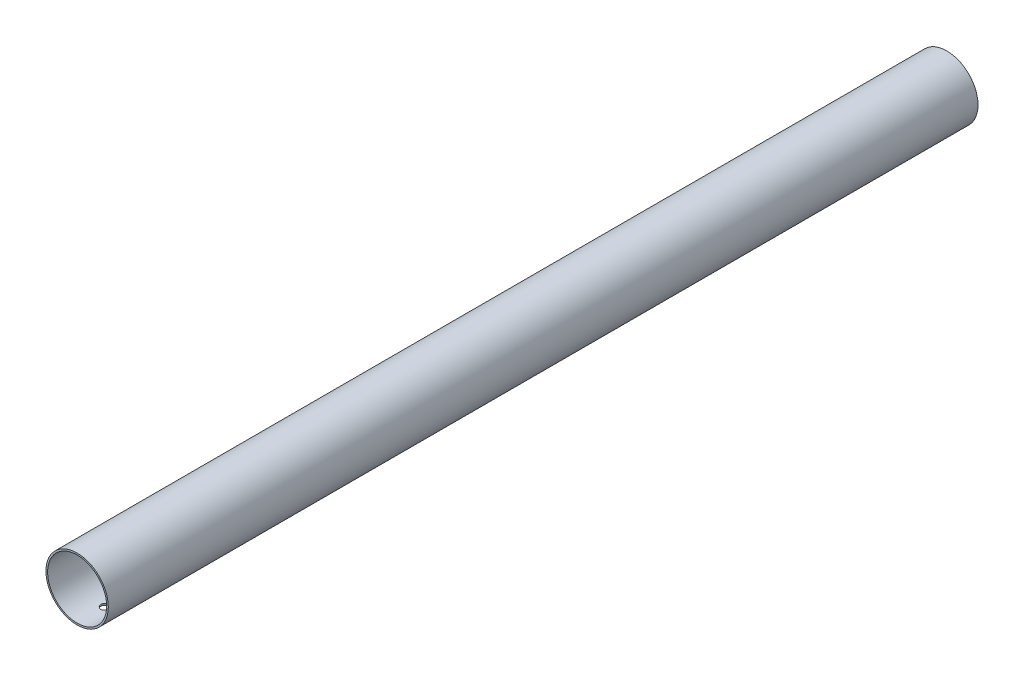
SolidWorks part; units mm, degrees
ref_plane "Plan de face" through (0, 0, 0) normal (0, 0, 1) x (1, 0, 0)
ref_plane "Plan de dessus" through (0, 0, 0) normal (0, 1, 0) x (1, 0, 0)
ref_plane "Plan de droite" through (0, 0, 0) normal (1, 0, 0) x (0, 0, -1)
sketch "Esquisse1" plane through (0, 0, 0) normal (0, 0, 1) x (1, 0, 0)
  circle A0 centre (0, 0) radius 18
  circle A1 centre (0, 0) radius 19
  dimension "D1" = 38
  dimension "D2" = 36
extrude "Boss.-Extru.1" add sketch "Esquisse1" along normal blind 530
sketch "Esquisse2" plane through (0, 0, 0) normal (0, 1, 0) x (1, 0, 0)
  circle A0 centre (0, -17) radius 2.5 construction
  circle A1 centre (0, -17) radius 2.5
extrude "Enlèv. mat.-Extru.1" cut sketch "Esquisse2" against normal through all
sketch "Esquisse4" plane through (0, 0, 0) normal (0, 1, 0) x (1, 0, 0)
  circle A0 centre (0, -513) radius 2.5 construction
  circle A1 centre (0, -513) radius 2.5
extrude "Enlèv. mat.-Extru.2" cut sketch "Esquisse4" against normal through all
